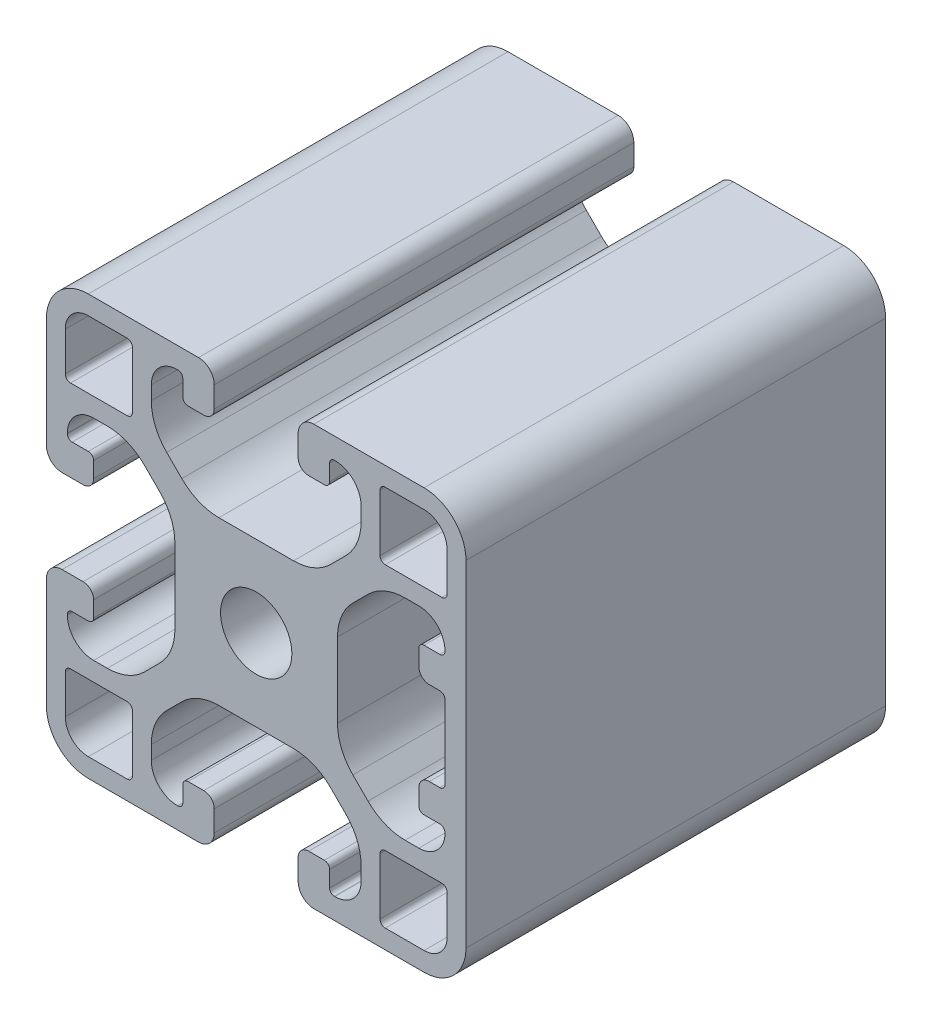
SolidWorks part; units mm, degrees
ref_plane "Piano frontale" through (0, 0, 0) normal (0, 0, 1) x (1, 0, 0)
ref_plane "Piano superiore" through (0, 0, 0) normal (0, 1, 0) x (1, 0, 0)
ref_plane "Piano destro" through (0, 0, 0) normal (1, 0, 0) x (0, 0, -1)
ref_plane "Piano1" through (0, 0, -340) normal (0, 0, -1) x (-1, 0, 0)
sketch "Schizzo1" plane through (0, 0, -340) normal (0, 0, -1) x (-1, 0, 0)
  line L0 (-12.3, -18.2) -> (-16, -18.2)
  line L1 (-18.2, -16) -> (-18.2, -12.3)
  line L2 (-17.7, -11.8) -> (-12.3, -11.8)
  line L3 (-11.8, -12.3) -> (-11.8, -17.7)
  line L4 (-11.8, 17.7) -> (-11.8, 12.3)
  line L5 (-12.3, 11.8) -> (-17.7, 11.8)
  line L6 (-18.2, 12.3) -> (-18.2, 16)
  line L7 (-16, 18.2) -> (-12.3, 18.2)
  line L8 (18.2, 16) -> (18.2, 12.3)
  line L9 (17.7, 11.8) -> (12.3, 11.8)
  line L10 (11.8, 12.3) -> (11.8, 17.7)
  line L11 (12.3, 18.2) -> (16, 18.2)
  line L12 (6.5, -15.5) -> (5, -15.5)
  line L13 (4, -16.5) -> (4, -18.5)
  line L14 (5.5, -20) -> (16, -20)
  line L15 (20, -16) -> (20, -5.5)
  line L16 (18.5, -4) -> (16.5, -4)
  line L17 (15.5, -5) -> (15.5, -6.5)
  line L18 (16, -7) -> (17.55, -7)
  line L19 (18, -7.45) -> (18, -7.5)
  line L20 (15.5, -10) -> (14.1924, -10)
  line L21 (10.6569, -8.5355) -> (9.2145, -7.0931)
  line L22 (7.75, -3.5576) -> (7.75, 3.5576)
  line L23 (9.2145, 7.0931) -> (10.6569, 8.5355)
  line L24 (14.1924, 10) -> (15.5, 10)
  line L25 (18, 7.5) -> (18, 7.45)
  line L26 (17.55, 7) -> (16, 7)
  line L27 (15.5, 6.5) -> (15.5, 5)
  line L28 (16.5, 4) -> (18.5, 4)
  line L29 (20, 5.5) -> (20, 16)
  line L30 (16, 20) -> (5.5, 20)
  line L31 (4, 18.5) -> (4, 16.5)
  line L32 (5, 15.5) -> (6.5, 15.5)
  line L33 (7, 16) -> (7, 17.55)
  line L34 (7.45, 18) -> (7.5, 18)
  line L35 (10, 15.5) -> (10, 14.1924)
  line L36 (8.5355, 10.6569) -> (7.0931, 9.2145)
  line L37 (3.5576, 7.75) -> (-3.5576, 7.75)
  line L38 (-7.0931, 9.2145) -> (-8.5355, 10.6569)
  line L39 (-10, 14.1924) -> (-10, 15.5)
  line L40 (-7.5, 18) -> (-7.45, 18)
  line L41 (-7, 17.55) -> (-7, 16)
  line L42 (-6.5, 15.5) -> (-5, 15.5)
  line L43 (-4, 16.5) -> (-4, 18.5)
  line L44 (-5.5, 20) -> (-16, 20)
  line L45 (-20, 16) -> (-20, -16)
  line L46 (-16, -20) -> (-5.5, -20)
  line L47 (-4, -18.5) -> (-4, -16.5)
  line L48 (-5, -15.5) -> (-6.5, -15.5)
  line L49 (-7, -16) -> (-7, -17.55)
  line L50 (-7.45, -18) -> (-7.5, -18)
  line L51 (-10, -15.5) -> (-10, -14.1924)
  line L52 (-8.5355, -10.6569) -> (-7.0931, -9.2145)
  line L53 (-3.5576, -7.75) -> (3.5576, -7.75)
  line L54 (7.0931, -9.2145) -> (8.5355, -10.6569)
  line L55 (10, -14.1924) -> (10, -15.5)
  line L56 (7.5, -18) -> (7.45, -18)
  line L57 (7, -17.55) -> (7, -16)
  line L58 (18.2, -12.3) -> (18.2, -16)
  line L59 (16, -18.2) -> (12.3, -18.2)
  line L60 (11.8, -17.7) -> (11.8, -12.3)
  line L61 (12.3, -11.8) -> (17.7, -11.8)
  line L62 (-16, 7) -> (-17.5, 7)
  line L63 (-15.5, 10) -> (-14.1924, 10)
  line L64 (-10.6569, 8.5355) -> (-9.2145, 7.0931)
  line L65 (-7.75, 3.5576) -> (-7.75, -3.5576)
  line L66 (-9.2145, -7.0931) -> (-10.6569, -8.5355)
  line L67 (-14.1924, -10) -> (-15.5, -10)
  line L68 (-17.5, -7) -> (-16, -7)
  line L69 (-15.5, -6.5) -> (-15.5, -5)
  line L70 (-16.5, -4) -> (-17.5, -4)
  line L71 (-18, -3.5) -> (-18, 3.5)
  line L72 (-17.5, 4) -> (-16.5, 4)
  line L73 (-15.5, 5) -> (-15.5, 6.5)
  arc A0 (-16, -18.2) -> (-18.2, -16) centre (-16, -16) cw
  arc A1 (-18.2, -12.3) -> (-17.7, -11.8) centre (-17.7, -12.3) cw
  arc A2 (-12.3, -11.8) -> (-11.8, -12.3) centre (-12.3, -12.3) cw
  arc A3 (-11.8, -17.7) -> (-12.3, -18.2) centre (-12.3, -17.7) cw
  arc A4 (-12.3, 18.2) -> (-11.8, 17.7) centre (-12.3, 17.7) cw
  arc A5 (-11.8, 12.3) -> (-12.3, 11.8) centre (-12.3, 12.3) cw
  arc A6 (-17.7, 11.8) -> (-18.2, 12.3) centre (-17.7, 12.3) cw
  arc A7 (-18.2, 16) -> (-16, 18.2) centre (-16, 16) cw
  arc A8 (16, 18.2) -> (18.2, 16) centre (16, 16) cw
  arc A9 (18.2, 12.3) -> (17.7, 11.8) centre (17.7, 12.3) cw
  arc A10 (12.3, 11.8) -> (11.8, 12.3) centre (12.3, 12.3) cw
  arc A11 (11.8, 17.7) -> (12.3, 18.2) centre (12.3, 17.7) cw
  arc A12 (5, -15.5) -> (4, -16.5) centre (5, -16.5) ccw
  arc A13 (4, -18.5) -> (5.5, -20) centre (5.5, -18.5) ccw
  arc A14 (16, -20) -> (20, -16) centre (16, -16) ccw
  arc A15 (20, -5.5) -> (18.5, -4) centre (18.5, -5.5) ccw
  arc A16 (16.5, -4) -> (15.5, -5) centre (16.5, -5) ccw
  arc A17 (15.5, -6.5) -> (16, -7) centre (16, -6.5) ccw
  arc A18 (17.55, -7) -> (18, -7.45) centre (17.55, -7.45) cw
  arc A19 (18, -7.5) -> (15.5, -10) centre (15.5, -7.5) cw
  arc A20 (14.1924, -10) -> (10.6569, -8.5355) centre (14.1924, -5) cw
  arc A21 (9.2145, -7.0931) -> (7.75, -3.5576) centre (12.75, -3.5576) cw
  arc A22 (7.75, 3.5576) -> (9.2145, 7.0931) centre (12.75, 3.5576) cw
  arc A23 (10.6569, 8.5355) -> (14.1924, 10) centre (14.1924, 5) cw
  arc A24 (15.5, 10) -> (18, 7.5) centre (15.5, 7.5) cw
  arc A25 (18, 7.45) -> (17.55, 7) centre (17.55, 7.45) cw
  arc A26 (16, 7) -> (15.5, 6.5) centre (16, 6.5) ccw
  arc A27 (15.5, 5) -> (16.5, 4) centre (16.5, 5) ccw
  arc A28 (18.5, 4) -> (20, 5.5) centre (18.5, 5.5) ccw
  arc A29 (20, 16) -> (16, 20) centre (16, 16) ccw
  arc A30 (5.5, 20) -> (4, 18.5) centre (5.5, 18.5) ccw
  arc A31 (4, 16.5) -> (5, 15.5) centre (5, 16.5) ccw
  arc A32 (6.5, 15.5) -> (7, 16) centre (6.5, 16) ccw
  arc A33 (7, 17.55) -> (7.45, 18) centre (7.45, 17.55) cw
  arc A34 (7.5, 18) -> (10, 15.5) centre (7.5, 15.5) cw
  arc A35 (10, 14.1924) -> (8.5355, 10.6569) centre (5, 14.1924) cw
  arc A36 (7.0931, 9.2145) -> (3.5576, 7.75) centre (3.5576, 12.75) cw
  arc A37 (-3.5576, 7.75) -> (-7.0931, 9.2145) centre (-3.5576, 12.75) cw
  arc A38 (-8.5355, 10.6569) -> (-10, 14.1924) centre (-5, 14.1924) cw
  arc A39 (-10, 15.5) -> (-7.5, 18) centre (-7.5, 15.5) cw
  arc A40 (-7.45, 18) -> (-7, 17.55) centre (-7.45, 17.55) cw
  arc A41 (-7, 16) -> (-6.5, 15.5) centre (-6.5, 16) ccw
  arc A42 (-5, 15.5) -> (-4, 16.5) centre (-5, 16.5) ccw
  arc A43 (-4, 18.5) -> (-5.5, 20) centre (-5.5, 18.5) ccw
  arc A44 (-16, 20) -> (-20, 16) centre (-16, 16) ccw
  arc A45 (-20, -16) -> (-16, -20) centre (-16, -16) ccw
  arc A46 (-5.5, -20) -> (-4, -18.5) centre (-5.5, -18.5) ccw
  arc A47 (-4, -16.5) -> (-5, -15.5) centre (-5, -16.5) ccw
  arc A48 (-6.5, -15.5) -> (-7, -16) centre (-6.5, -16) ccw
  arc A49 (-7, -17.55) -> (-7.45, -18) centre (-7.45, -17.55) cw
  arc A50 (-7.5, -18) -> (-10, -15.5) centre (-7.5, -15.5) cw
  arc A51 (-10, -14.1924) -> (-8.5355, -10.6569) centre (-5, -14.1924) cw
  arc A52 (-7.0931, -9.2145) -> (-3.5576, -7.75) centre (-3.5576, -12.75) cw
  arc A53 (3.5576, -7.75) -> (7.0931, -9.2145) centre (3.5576, -12.75) cw
  arc A54 (8.5355, -10.6569) -> (10, -14.1924) centre (5, -14.1924) cw
  arc A55 (10, -15.5) -> (7.5, -18) centre (7.5, -15.5) cw
  arc A56 (7.45, -18) -> (7, -17.55) centre (7.45, -17.55) cw
  arc A57 (7, -16) -> (6.5, -15.5) centre (6.5, -16) ccw
  arc A58 (17.7, -11.8) -> (18.2, -12.3) centre (17.7, -12.3) cw
  arc A59 (18.2, -16) -> (16, -18.2) centre (16, -16) cw
  arc A60 (12.3, -18.2) -> (11.8, -17.7) centre (12.3, -17.7) cw
  arc A61 (11.8, -12.3) -> (12.3, -11.8) centre (12.3, -12.3) cw
  circle A62 centre (0, 0) radius 3.4
  arc A63 (-15.5, 6.5) -> (-16, 7) centre (-16, 6.5) ccw
  arc A64 (-17.5, 7) -> (-18, 7.5) centre (-17.5, 7.5) cw
  arc A65 (-18, 7.5) -> (-15.5, 10) centre (-15.5, 7.5) cw
  arc A66 (-14.1924, 10) -> (-10.6569, 8.5355) centre (-14.1924, 5) cw
  arc A67 (-9.2145, 7.0931) -> (-7.75, 3.5576) centre (-12.75, 3.5576) cw
  arc A68 (-7.75, -3.5576) -> (-9.2145, -7.0931) centre (-12.75, -3.5576) cw
  arc A69 (-10.6569, -8.5355) -> (-14.1924, -10) centre (-14.1924, -5) cw
  arc A70 (-15.5, -10) -> (-18, -7.5) centre (-15.5, -7.5) cw
  arc A71 (-18, -7.5) -> (-17.5, -7) centre (-17.5, -7.5) cw
  arc A72 (-16, -7) -> (-15.5, -6.5) centre (-16, -6.5) ccw
  arc A73 (-15.5, -5) -> (-16.5, -4) centre (-16.5, -5) ccw
  arc A74 (-17.5, -4) -> (-18, -3.5) centre (-17.5, -3.5) cw
  arc A75 (-18, 3.5) -> (-17.5, 4) centre (-17.5, 3.5) cw
  arc A76 (-16.5, 4) -> (-15.5, 5) centre (-16.5, 5) ccw
extrude "Estrusione-Estrusione1" add sketch "Schizzo1" against normal blind 40
